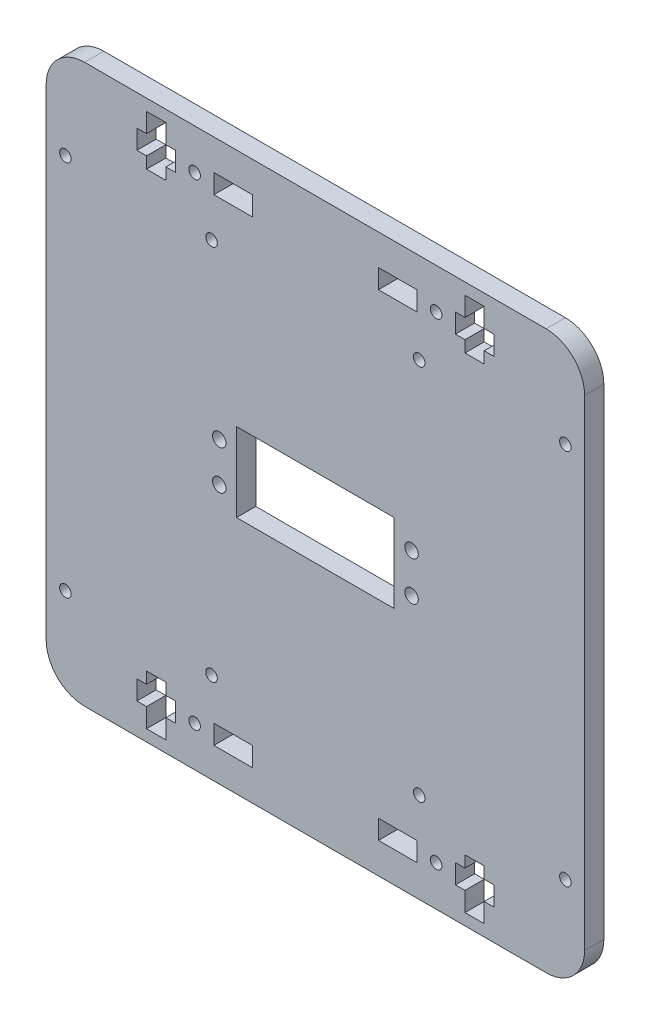
SolidWorks part; units mm, degrees
ref_plane "Front Plane" through (0, 0, 0) normal (0, 0, 1) x (1, 0, 0)
ref_plane "Top Plane" through (0, 0, 0) normal (0, 1, 0) x (1, 0, 0)
ref_plane "Right Plane" through (0, 0, 0) normal (1, 0, 0) x (0, 0, -1)
sketch "Sketch1" plane through (0, 0, 0) normal (0, 0, 1) x (1, 0, 0)
  line L0 (40.144, -13) -> (40.144, -137) construction
  line L1 (70, -147.5) -> (-70, -147.5)
  line L2 (70, -147.5) -> (70, -2.5)
  line L3 (70, -2.5) -> (-70, -2.5)
  line L4 (-70, -147.5) -> (-70, -2.5)
  line L5 (26.394, -139.5) -> (16.394, -139.5) construction
  line L6 (0, -125) -> (0, -147.5) construction
  line L7 (16.394, -125) -> (-16.394, -125) construction
  line L8 (0, -75) -> (70, -75) construction
  dimension "D1" = 8
  dimension "D2" = 140
extrude "Boss-Extrude1" add sketch "Sketch1" against normal blind 5
sketch "Sketch2" plane through (0, 0, 0) normal (0, 0, 1) x (1, 0, 0)
  line L3 (43.894, -134.5) -> (43.894, -131.5)
  line L4 (38.894, -139.5) -> (38.894, -144.5)
  line L5 (43.894, -144.5) -> (43.894, -131.5)
  line L6 (43.894, -131.5) -> (38.894, -131.5)
  line L7 (38.894, -131.5) -> (38.894, -144.5)
  line L8 (38.894, -144.5) -> (43.894, -144.5)
  line L9 (43.894, -144.5) -> (43.894, -139.5)
  line L10 (43.894, -131.5) -> (38.894, -131.5)
  line L11 (38.894, -131.5) -> (38.894, -134.5)
  line L12 (38.894, -144.5) -> (43.894, -144.5)
  line L13 (38.894, -139.5) -> (38.894, -134.5)
  line L14 (38.894, -134.5) -> (36.394, -134.5)
  line L15 (36.394, -134.5) -> (36.394, -139.5)
  line L16 (36.394, -139.5) -> (38.894, -139.5)
  line L18 (38.894, -134.5) -> (36.394, -134.5)
  line L19 (36.394, -134.5) -> (36.394, -139.5)
  line L20 (36.394, -139.5) -> (38.894, -139.5)
  line L21 (70, -75) -> (-70, -75) construction
  line L22 (43.894, -134.5) -> (43.894, -139.5)
  line L23 (43.894, -139.5) -> (46.394, -139.5)
  line L24 (46.394, -139.5) -> (46.394, -134.5)
  line L25 (46.394, -134.5) -> (43.894, -134.5)
  line L27 (43.894, -139.5) -> (46.394, -139.5)
  line L28 (46.394, -139.5) -> (46.394, -134.5)
  line L29 (46.394, -134.5) -> (43.894, -134.5)
  line L30 (70, -147.5) -> (70, -2.5) construction
  line L31 (16.394, -139.5) -> (26.394, -139.5)
  line L32 (26.394, -139.5) -> (26.394, -134.5)
  line L33 (26.394, -134.5) -> (16.394, -134.5)
  line L34 (16.394, -134.5) -> (16.394, -139.5)
  line L35 (16.394, -139.5) -> (26.394, -139.5)
  line L36 (26.394, -139.5) -> (26.394, -134.5)
  line L37 (26.394, -134.5) -> (16.394, -134.5)
  line L38 (16.394, -134.5) -> (16.394, -139.5)
  line L39 (-70, -2.5) -> (-70, -147.5) construction
  line L40 (0, -147.5) -> (0, -2.5) construction
  line L41 (-70, -147.5) -> (70, -147.5) construction
  line L42 (70, -2.5) -> (-70, -2.5) construction
  line L43 (-16.394, -134.5) -> (-16.394, -139.5)
  line L44 (-26.394, -134.5) -> (-16.394, -134.5)
  line L45 (-26.394, -139.5) -> (-26.394, -134.5)
  line L46 (-16.394, -139.5) -> (-26.394, -139.5)
  line L47 (-46.394, -134.5) -> (-43.894, -134.5)
  line L48 (-46.394, -139.5) -> (-46.394, -134.5)
  line L49 (-43.894, -139.5) -> (-46.394, -139.5)
  line L50 (-36.394, -139.5) -> (-38.894, -139.5)
  line L51 (-36.394, -134.5) -> (-36.394, -139.5)
  line L52 (-38.894, -134.5) -> (-36.394, -134.5)
  line L53 (-38.894, -144.5) -> (-43.894, -144.5)
  line L54 (-38.894, -131.5) -> (-38.894, -134.5)
  line L55 (-43.894, -131.5) -> (-38.894, -131.5)
  line L56 (-43.894, -144.5) -> (-43.894, -139.5)
  line L57 (-38.894, -139.5) -> (-38.894, -144.5)
  line L58 (-43.894, -134.5) -> (-43.894, -131.5)
  line L59 (-43.894, -15.5) -> (-43.894, -18.5)
  line L60 (-38.894, -10.5) -> (-38.894, -5.5)
  line L61 (-43.894, -5.5) -> (-43.894, -10.5)
  line L62 (-43.894, -18.5) -> (-38.894, -18.5)
  line L63 (-38.894, -18.5) -> (-38.894, -15.5)
  line L64 (-38.894, -5.5) -> (-43.894, -5.5)
  line L65 (-38.894, -15.5) -> (-36.394, -15.5)
  line L66 (-36.394, -15.5) -> (-36.394, -10.5)
  line L67 (-36.394, -10.5) -> (-38.894, -10.5)
  line L68 (-43.894, -10.5) -> (-46.394, -10.5)
  line L69 (-46.394, -10.5) -> (-46.394, -15.5)
  line L70 (-46.394, -15.5) -> (-43.894, -15.5)
  line L71 (-16.394, -10.5) -> (-26.394, -10.5)
  line L72 (-26.394, -10.5) -> (-26.394, -15.5)
  line L73 (-26.394, -15.5) -> (-16.394, -15.5)
  line L74 (-16.394, -15.5) -> (-16.394, -10.5)
  line L75 (16.394, -15.5) -> (16.394, -10.5)
  line L76 (26.394, -15.5) -> (16.394, -15.5)
  line L77 (26.394, -10.5) -> (26.394, -15.5)
  line L78 (16.394, -10.5) -> (26.394, -10.5)
  line L79 (46.394, -15.5) -> (43.894, -15.5)
  line L80 (46.394, -10.5) -> (46.394, -15.5)
  line L81 (43.894, -10.5) -> (46.394, -10.5)
  line L82 (36.394, -10.5) -> (38.894, -10.5)
  line L83 (36.394, -15.5) -> (36.394, -10.5)
  line L84 (38.894, -15.5) -> (36.394, -15.5)
  line L85 (38.894, -5.5) -> (43.894, -5.5)
  line L86 (38.894, -18.5) -> (38.894, -15.5)
  line L87 (43.894, -18.5) -> (38.894, -18.5)
  line L88 (43.894, -5.5) -> (43.894, -10.5)
  line L89 (38.894, -10.5) -> (38.894, -5.5)
  line L90 (43.894, -15.5) -> (43.894, -18.5)
  dimension "D1" = 0
  dimension "D2" = 0
  dimension "D3" = 0
  dimension "D4" = 0
extrude "Cut-Extrude1" cut sketch "Sketch2" against normal through all
sketch "Sketch3" plane through (0, 0, 0) normal (0, 0, 1) x (1, 0, 0)
  line L0 (29.894, -137) -> (32.894, -137) construction
  line L1 (0, -2.5) -> (0, -147.5) construction
  line L2 (70, -2.5) -> (-70, -2.5) construction
  line L3 (-70, -147.5) -> (70, -147.5) construction
  line L4 (29.894, -139.5) -> (32.894, -139.5)
  line L5 (32.894, -139.5) -> (32.894, -134.5)
  line L6 (32.894, -134.5) -> (29.894, -134.5)
  line L7 (29.894, -134.5) -> (29.894, -139.5)
  line L8 (29.894, -139.5) -> (32.894, -139.5) construction
  line L9 (32.894, -139.5) -> (32.894, -134.5) construction
  line L10 (32.894, -134.5) -> (29.894, -134.5) construction
  line L11 (29.894, -134.5) -> (29.894, -139.5) construction
  line L12 (-70, -75) -> (70, -75) construction
  line L13 (-70, -2.5) -> (-70, -147.5) construction
  line L14 (70, -147.5) -> (70, -2.5) construction
  circle A0 centre (31.394, -137) radius 1.5
  circle A1 centre (-31.394, -137) radius 1.5
  circle A2 centre (31.394, -13) radius 1.5
  circle A3 centre (-31.394, -13) radius 1.5
  dimension "D1" = 0
extrude "Cut-Extrude2" cut sketch "Sketch3" against normal blind 5
sketch "Sketch4" plane through (0, 0, 0) normal (0, 0, 1) x (1, 0, 0)
  line L0 (70, -75) -> (-70, -75) construction
  line L1 (70, -147.5) -> (70, -2.5) construction
  line L2 (-70, -2.5) -> (-70, -147.5) construction
  line L3 (65, -124) -> (26.8057, -124) construction
  line L4 (0, -147.5) -> (0, -75) construction
  line L5 (-70, -147.5) -> (70, -147.5) construction
  circle A0 centre (65, -124) radius 1.5
  circle A1 centre (27, -124) radius 1.5
  circle A2 centre (27, -26) radius 1.5
  circle A3 centre (65, -26) radius 1.5
  circle A4 centre (-27, -26) radius 1.5
  circle A5 centre (-65, -26) radius 1.5
  circle A6 centre (-65, -124) radius 1.5
  circle A7 centre (-27, -124) radius 1.5
  dimension "D1" = 98
  dimension "D3" = 3
  dimension "D4" = 38
  dimension "D2" = 5
extrude "Cut-Extrude3" cut sketch "Sketch4" against normal through all
sketch "Sketch5" plane through (0, 0, 0) normal (0, 0, 1) x (1, 0, 0)
  line L0 (70, -75) -> (-70, -75) construction
  line L1 (70, -147.5) -> (70, -2.5) construction
  line L2 (-70, -2.5) -> (-70, -147.5) construction
  line L3 (0, -147.5) -> (0, -2.5) construction
  line L4 (-70, -147.5) -> (70, -147.5) construction
  line L5 (70, -2.5) -> (-70, -2.5) construction
  line L6 (25, -75) -> (25, -92.9802) construction
  line L7 (20.5, -64.75) -> (-20.5, -64.75)
  line L8 (20.5, -64.75) -> (20.5, -85.25)
  line L9 (20.5, -85.25) -> (-20.5, -85.25)
  line L10 (-20.5, -64.75) -> (-20.5, -85.25)
  line L11 (20.5, -64.75) -> (-20.5, -85.25) construction
  line L12 (20.5, -85.25) -> (-20.5, -64.75) construction
  circle A1 centre (25, -80.1) radius 1.75
  circle A2 centre (25, -69.9) radius 1.75
  circle A3 centre (-25, -80.1) radius 1.75
  circle A4 centre (-25, -69.9) radius 1.75
  point P12 (0, -75)
  dimension "D3" = 4.5
  dimension "D5" = 3.5
  dimension "D1" = 41
  dimension "D2" = 20.5
  dimension "D4" = 10.2
extrude "Cut-Extrude4" cut sketch "Sketch5" against normal through all
fillet "Fillet1" radius 10 4 edges at (70, -147.5, -2.5) (70, -2.5, -2.5) (-70, -2.5, -2.5) (-70, -147.5, -2.5)
